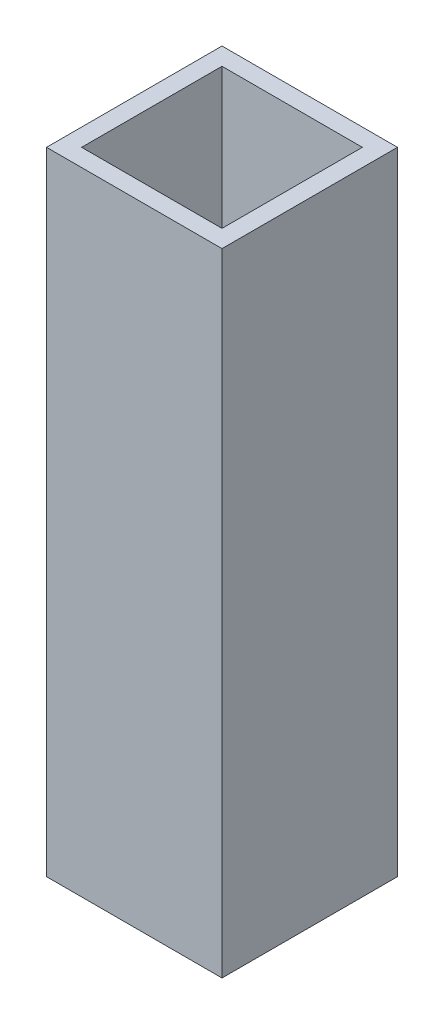
SolidWorks part; units mm, degrees
material "Silicon Dioxide"
ref_plane "Front Plane" through (0, 0, 0) normal (0, 0, 1) x (1, 0, 0)
ref_plane "Top Plane" through (0, 0, 0) normal (0, 1, 0) x (1, 0, 0)
ref_plane "Right Plane" through (0, 0, 0) normal (1, 0, 0) x (0, 0, -1)
other "Configuration Table"
sketch "Sketch1" plane through (0, 0, 0) normal (0, 1, 0) x (1, 0, 0)
  line L1 (-6.25, -6.25) -> (6.25, -6.25)
  line L2 (-6.25, -6.25) -> (-6.25, 6.25)
  line L3 (-6.25, 6.25) -> (6.25, 6.25)
  line L4 (6.25, -6.25) -> (6.25, 6.25)
  line L5 (-6.25, -6.25) -> (6.25, 6.25) construction
  line L6 (-6.25, 6.25) -> (6.25, -6.25) construction
  point P6 (0, 0)
  dimension "D1" = 12.5
  dimension "D2" = 12.5
extrude "Cuvette_Body" add sketch "Sketch1" along normal blind 45
sketch "Sketch2" plane through (0, 0, 0) normal (0, 1, 0) x (1, 0, 0)
  line L0 (-5, -5) -> (5, -5)
  line L1 (5, -5) -> (5, 5)
  line L2 (5, 5) -> (-5, 5)
  line L3 (-5, 5) -> (-5, -5)
extrude "Sample_Space" cut sketch "Sketch2" against normal blind 43.75 from offset 45
equation "\"Jar_OD\"= 90  'ASSUMED - Part G fallback - jar outer diameter"
equation "\"Jar_H\"= 120  'ASSUMED - Part G fallback - jar height"
equation "\"Pump_L\"= 45  'ASSUMED - Part G fallback"
equation "\"Pump_W\"= 24  'ASSUMED - Part G fallback"
equation "\"Pump_H\"= 33  'ASSUMED - Part G fallback"
equation "\"Pump_Outlet_OD\"= 7.5  'ASSUMED - Part G fallback"
equation "\"Tube_OD\"= 8  'ASSUMED - Part G fallback"
equation "\"Tube_ID\"= 6  'ASSUMED - Part G fallback"
equation "\"TDS_Body_Dia\"= 12  'ASSUMED - Part G fallback"
equation "\"TDS_Wet_Len\"= 45  'ASSUMED - Part G fallback - length in water"
equation "\"DS_Tube_Dia\"= 6  'ASSUMED - Part G fallback"
equation "\"DS_Tube_Len\"= 50  'ASSUMED - Part G fallback"
equation "\"ORP_Body_Dia\"= 12  'ASSUMED - Part G fallback"
equation "\"ORP_Body_Len\"= 150  'ASSUMED - Part G fallback"
equation "\"ORP_Cap_Dia\"= 16  'ASSUMED - Part G fallback"
equation "\"Turb_W\"= 33  'ASSUMED - Part G fallback - head width"
equation "\"Turb_D\"= 28  'ASSUMED - Part G fallback - head depth"
equation "\"Turb_H\"= 30  'ASSUMED - Part G fallback - head height"
equation "\"Turb_Slot_W\"= 10  'ASSUMED - Part G fallback - slot width"
equation "\"Flow_L\"= 62  'ASSUMED - Part G fallback YF-S201"
equation "\"Flow_W\"= 36  'ASSUMED - Part G fallback"
equation "\"Flow_H\"= 35  'ASSUMED - Part G fallback"
equation "\"Thread_G12_OD\"= 20.955  'ASSUMED - Part G fallback thread G1/2 (major diameter)"
equation "\"Valve_L\"= 75  'ASSUMED - Part G fallback"
equation "\"Valve_W\"= 45  'ASSUMED - Part G fallback"
equation "\"Valve_H\"= 60  'ASSUMED - Part G fallback"
equation "\"Tee_L\"= 40  'ASSUMED - Part G fallback - overall length"
equation "\"Tee_Branch_L\"= 25  'ASSUMED - Part G fallback"
equation "\"Tee_OD\"= 12  'ASSUMED - Part G fallback"
equation "\"Cuv_W\"= 12.5  'ASSUMED - old R3 cuvette (station suppressed in SS4)"
equation "\"Cuv_D\"= 12.5  'ASSUMED - old R3 cuvette (station suppressed in SS4)"
equation "\"Cuv_H\"= 45  'ASSUMED - old R3 cuvette (station suppressed in SS4)"
equation "\"LED_Board_L\"= 20  'ASSUMED - Part G fallback"
equation "\"LED_Board_W\"= 20  'ASSUMED - Part G fallback - LED at centre"
equation "\"GUVA_L\"= 20  'ASSUMED - Part G fallback"
equation "\"GUVA_W\"= 12  'ASSUMED - Part G fallback - sensor at centre"
equation "\"Reed_L\"= 27  'ASSUMED - Part G fallback MC-38 half"
equation "\"Reed_W\"= 14  'ASSUMED - Part G fallback"
equation "\"Reed_H\"= 8  'ASSUMED - Part G fallback"
equation "\"ESP_L\"= 51  'ASSUMED - Part G fallback"
equation "\"ESP_W\"= 28  'ASSUMED - Part G fallback"
equation "\"TFT_L\"= 58  'ASSUMED - Part G fallback - board"
equation "\"TFT_W\"= 35  'ASSUMED - Part G fallback - board"
equation "\"TFT_Win_L\"= 35  'ASSUMED - Part G fallback - visible window"
equation "\"TFT_Win_W\"= 28  'ASSUMED - Part G fallback - visible window"
equation "\"Relay_L\"= 50  'ASSUMED - Part G fallback"
equation "\"Relay_W\"= 26  'ASSUMED - Part G fallback"
equation "\"Relay_H\"= 19  'ASSUMED - Part G fallback"
equation "\"Mosfet_L\"= 34  'ASSUMED - Part G fallback"
equation "\"Mosfet_W\"= 17  'ASSUMED - Part G fallback"
equation "\"Mosfet_H\"= 12  'ASSUMED - Part G fallback"
equation "\"TDS_Board_L\"= 42  'ASSUMED - Part G fallback"
equation "\"TDS_Board_W\"= 32  'ASSUMED - Part G fallback"
equation "\"Turb_Board_L\"= 38  'ASSUMED - Part G fallback"
equation "\"Turb_Board_W\"= 28  'ASSUMED - Part G fallback"
equation "\"BNC_Thread_Dia\"= 9.5  'ASSUMED - Part G fallback"
equation "\"Plate_L\"= 420  'ASSUMED - Part G fallback"
equation "\"Plate_W\"= 297  'ASSUMED - Part G fallback"
equation "\"Plate_T\"= 6  'ASSUMED - Part G fallback"
equation "\"Probe_Clr\"= 0.3  'DESIGN VALUE - Part C rule 3 - printed probe hole = diameter + 0.3"
equation "\"Cuv_Clr\"= 0.2  'DESIGN VALUE - Part C rule 3 - cuvette pocket = size + 0.2"
equation "\"Label_H\"= 0.6  'DESIGN VALUE - Part D - raised label height"
equation "\"D1@Sketch1\" = \"Cuv_W\""
equation "\"D2@Sketch1\" = \"Cuv_D\""
equation "\"D1@Cuvette_Body\" = \"Cuv_H\""
equation "\"Booster_L\"= 150  'ASSUMED - Part G fallback - booster pump"
equation "\"Booster_W\"= 95  'ASSUMED - Part G fallback"
equation "\"Booster_H\"= 100  'ASSUMED - Part G fallback"
equation "\"PTube_OD\"= 6.35  'ASSUMED - Part G fallback - product tube 1/4 inch"
equation "\"Qz_Out\"= 12  'ASSUMED - Part G fallback - quartz channel outside square"
equation "\"Qz_Path\"= 10  'ASSUMED - Part G fallback - quartz channel inside light path"
equation "\"Qz_L\"= 40  'ASSUMED - Part G fallback - quartz channel length"
equation "\"LED860_Dia\"= 5  'ASSUMED - Part G fallback - 860 nm LED"
equation "\"BPW_L\"= 5.4  'ASSUMED - Part G fallback - BPW34"
equation "\"BPW_W\"= 4.3  'ASSUMED - Part G fallback - BPW34"
equation "\"Cart_Dia\"= 50  'ASSUMED - Part G fallback - sediment and pre-carbon cartridges"
equation "\"Cart_L\"= 255  'ASSUMED - Part G fallback"
equation "\"UF_Dia\"= 50  'ASSUMED - Part G fallback - UF cartridge"
equation "\"UF_L\"= 260  'ASSUMED - Part G fallback"
equation "\"RO_Dia\"= 62  'ASSUMED - Part G fallback - RO membrane housing"
equation "\"RO_L\"= 300  'ASSUMED - Part G fallback"
equation "\"UVC_Dia\"= 40  'ASSUMED - Part G fallback - UV-C chamber"
equation "\"UVC_L\"= 300  'ASSUMED - Part G fallback"
equation "\"Tank_W\"= 260  'ASSUMED - Part G fallback - storage tank"
equation "\"Tank_D\"= 160  'ASSUMED - Part G fallback"
equation "\"Tank_H\"= 300  'ASSUMED - Part G fallback"
equation "\"Cab_W\"= 400  'ASSUMED - Part G fallback - purifier cabinet"
equation "\"Cab_D\"= 270  'ASSUMED - Part G fallback"
equation "\"Cab_H\"= 560  'ASSUMED - Part G fallback"
equation "\"ORP_Board_L\"= 40  'ASSUMED - Part G fallback - ORP buffer board"
equation "\"ORP_Board_W\"= 30  'ASSUMED - Part G fallback"
equation "\"Opt_Board_L\"= 50  'ASSUMED - Part G fallback - optical front-end board"
equation "\"Opt_Board_W\"= 40  'ASSUMED - Part G fallback"
equation "\"Buck_L\"= 43  'ASSUMED - Part G fallback - 12 V to 5 V buck module"
equation "\"Buck_W\"= 21  'ASSUMED - Part G fallback"
equation "\"Buck_H\"= 14  'ASSUMED - Part G fallback"
equation "\"BB_L\"= 165  'ASSUMED - Part G fallback - breadboard (As_Built_R3 only)"
equation "\"BB_W\"= 55  'ASSUMED - Part G fallback"
equation "\"BB_H\"= 10  'ASSUMED - Part G fallback"
